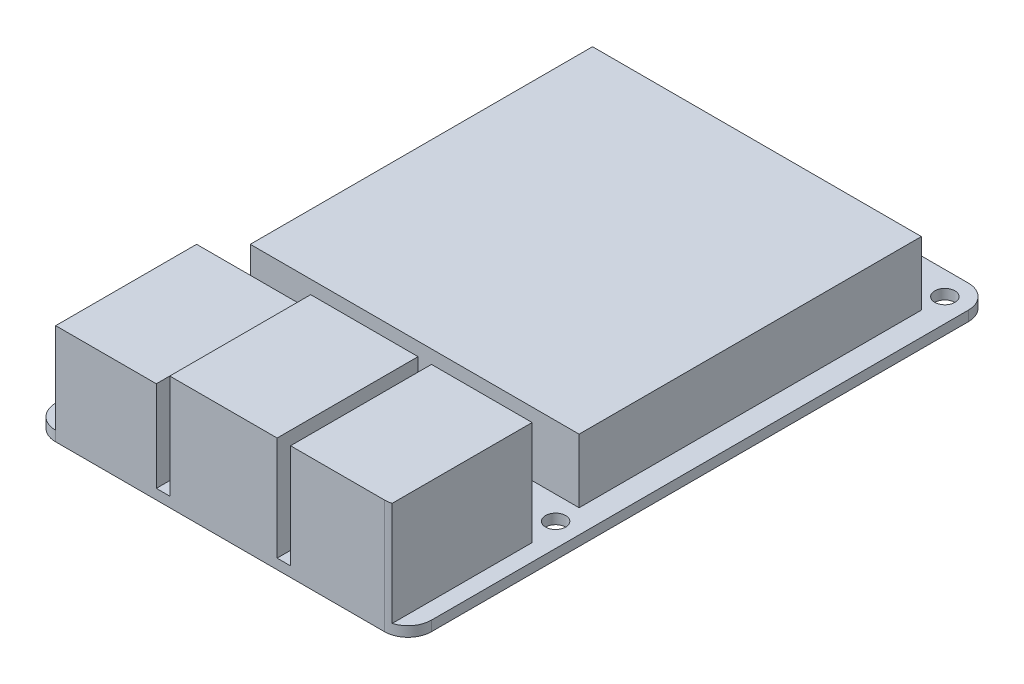
SolidWorks part; units mm, degrees
ref_plane "Спереди" through (0, 0, 0) normal (0, 0, 1) x (1, 0, 0)
ref_plane "Сверху" through (0, 0, 0) normal (0, 1, 0) x (1, 0, 0)
ref_plane "Справа" through (0, 0, 0) normal (1, 0, 0) x (0, 0, -1)
sketch "Эскиз1" plane through (0, 0, 0) normal (0, 1, 0) x (1, 0, 0)
  line L0 (3.5, 0) -> (52.5, 0)
  line L1 (0, 3.5) -> (0, 83.5)
  line L2 (3.5, 87) -> (52.5, 87)
  line L3 (56, 83.5) -> (56, 3.5)
  line L4 (3.5, 83.5) -> (3.5, 25.5) construction
  line L5 (3.5, 25.5) -> (52.5, 25.5) construction
  arc A0 (52.5, 87) -> (56, 83.5) centre (52.5, 83.5) cw
  arc A1 (52.5, 0) -> (56, 3.5) centre (52.5, 3.5) ccw
  arc A2 (3.5, 0) -> (0, 3.5) centre (3.5, 3.5) cw
  arc A3 (0, 83.5) -> (3.5, 87) centre (3.5, 83.5) cw
  circle A4 centre (3.5, 83.5) radius 1.5
  circle A5 centre (52.5, 83.5) radius 1.5
  circle A6 centre (52.5, 25.5) radius 1.5
  circle A7 centre (3.5, 25.5) radius 1.5
  point P11 (0, 0)
  dimension "D1" = 3.5
extrude "Бобышка-Вытянуть1" add sketch "Эскиз1" along normal blind 1.5
sketch "Эскиз2" plane through (0, 1.5, 0) normal (0, 1, 0) x (1, 0, 0)
  line L0 (28, 0) -> (20.5, 0)
  line L1 (3.5, 0) -> (52.5, 0) construction
  line L2 (2.5, 0) -> (2.5, 21)
  line L3 (2.5, 21) -> (18.5, 21)
  line L4 (53.5, 21) -> (53.5, 0)
  line L5 (53.5, 0) -> (38.5, 0)
  line L6 (2.5, 21) -> (18.5, 21)
  line L7 (18.5, 21) -> (18.5, 0)
  line L9 (20.5, 0) -> (20.5, 21)
  line L10 (20.5, 21) -> (36.5, 21)
  line L11 (36.5, 21) -> (36.5, 0)
  line L13 (38.5, 0) -> (38.5, 21)
  line L14 (20.5, 21) -> (36.5, 21)
  line L15 (38.5, 21) -> (53.5, 21)
  line L16 (36.5, 0) -> (28, 0)
  line L17 (18.5, 0) -> (2.5, 0)
  line M8 (3.5, 0) -> (52.5, 0)
  arc M9 (52.5, 0) -> (56, 3.5) centre (52.5, 3.5) ccw
extrude "Бобышка-Вытянуть2" add sketch "Эскиз2" along normal blind 15.5 contours L11 L10 L9 M8 | L15 L13 L4 M8 M9
sketch "Эскиз3" plane through (0, 1.5, 0) normal (0, 1, 0) x (1, 0, 0)
  line L1 (52.5, 80) -> (3.5, 80)
  line L2 (3.5, 80) -> (3.5, 29)
  line L3 (3.5, 29) -> (52.5, 29)
  line L4 (52.5, 29) -> (52.5, 80)
extrude "Бобышка-Вытянуть3" add sketch "Эскиз3" along normal blind 9.5
sketch "Эскиз4" plane through (0, 1.5, 0) normal (0, 1, 0) x (1, 0, 0)
  line L0 (3.5, 21) -> (3.5, 0)
  line L1 (20.5, 0) -> (18.5, 0)
  line L2 (3.5, 0) -> (20.5, 0) construction
  line L3 (18.5, 0) -> (18.5, 21)
  line L4 (18.5, 21) -> (3.5, 21)
  line L16 (36.5, 0) -> (38.5, 0)
  line L17 (38.5, 0) -> (38.5, 21)
  line L18 (38.5, 21) -> (53.5, 21)
  line L19 (53.5, 21) -> (53.5, 0.1459)
  line L20 (56, 3.5) -> (56, 83.5)
  line L21 (52.5, 87) -> (3.5, 87)
  line L22 (0, 83.5) -> (0, 3.5)
  line L23 (3.5, 0) -> (20.5, 0)
  line L24 (20.5, 0) -> (20.5, 21)
  line L25 (20.5, 21) -> (36.5, 21)
  line L26 (36.5, 21) -> (36.5, 0)
  line L34 (3.5, 0) -> (20.5, 0)
  arc A4 (53.5, 0.1459) -> (56, 3.5) centre (52.5, 3.5) ccw
  arc A5 (56, 83.5) -> (52.5, 87) centre (52.5, 83.5) ccw
  arc A6 (3.5, 87) -> (0, 83.5) centre (3.5, 83.5) ccw
  arc A7 (0, 3.5) -> (3.5, 0) centre (3.5, 3.5) ccw
  line M29 (3.5, 0) -> (20.5, 0)
  dimension "D1" = 0
extrude "Бобышка-Вытянуть4" add sketch "Эскиз4" along normal blind 13.5 contours L3 L4 L0 M29
